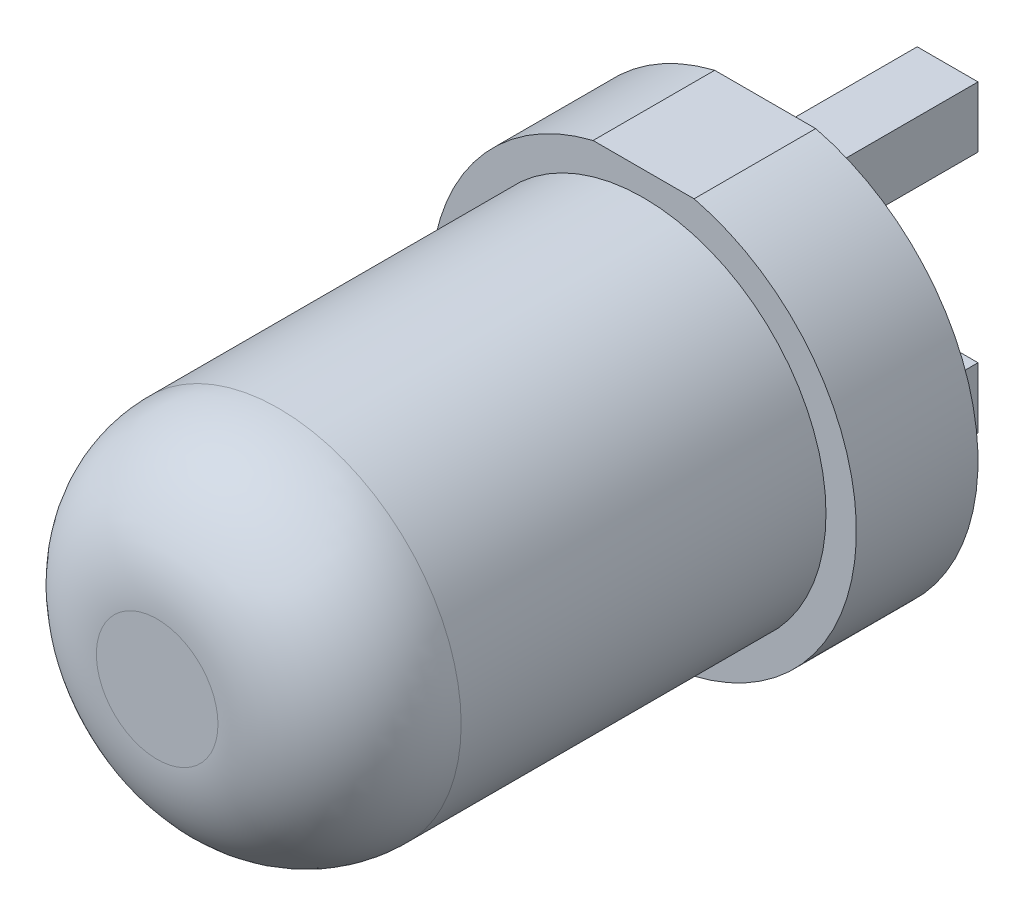
SolidWorks part; units mm, degrees
ref_plane "Front Plane" through (0, 0, 0) normal (0, 0, 1) x (1, 0, 0)
ref_plane "Top Plane" through (0, 0, 0) normal (0, 1, 0) x (1, 0, 0)
ref_plane "Right Plane" through (0, 0, 0) normal (1, 0, 0) x (0, 0, -1)
sketch "Sketch1" plane through (0, 0, 0) normal (0, 0, 1) x (1, 0, 0)
  circle A0 centre (0, 0) radius 1.75
  dimension "D1" = 3.5
extrude "Extrude1" add sketch "Sketch1" along normal mid plane 1
sketch "Sketch2" plane through (0, 0, 0.5) normal (0, 0, 1) x (1, 0, 0)
  circle A0 centre (0, 0) radius 1.5
  dimension "D1" = 3
extrude "Extrude2" add sketch "Sketch2" along normal blind 4
fillet "Fillet2" radius 1 1 edges at (1.5, 0, 4.5)
ref_plane "Plane1" through (0, 3, 0) normal (0, 1, 0) x (-1, 0, 0)
sketch "Sketch4" plane through (0, 3, 0) normal (0, 1, 0) x (-1, 0, 0)
  line L1 (4.5989, -2.7325) -> (-8.4821, -2.7325)
  line L2 (4.5989, -2.7325) -> (4.5989, 3.078)
  line L3 (4.5989, 3.078) -> (-8.4821, 3.078)
  line L4 (-8.4821, -2.7325) -> (-8.4821, 3.078)
extrude "Extrude3" cut sketch "Sketch4" against normal blind 1.3
ref_plane "Plane2" through (0, 0, -0.5) normal (0, 0, -1) x (-1, 0, 0)
sketch "Sketch5" plane through (0, 0, -0.5) normal (0, 0, -1) x (-1, 0, 0)
  line L1 (-0.25, 1.2) -> (0.25, 1.2)
  line L2 (-0.25, 1.2) -> (-0.25, 0.7)
  line L3 (-0.25, 0.7) -> (0.25, 0.7)
  line L4 (0.25, 1.2) -> (0.25, 0.7)
  line L5 (-0.25, -0.8) -> (0.25, -0.8)
  line L6 (-0.25, -0.8) -> (-0.25, -1.3)
  line L7 (-0.25, -1.3) -> (0.25, -1.3)
  line L8 (0.25, -0.8) -> (0.25, -1.3)
  point P10 (0, 1.2)
  point P11 (0, -1.3)
  dimension "D1" = 2.5
  dimension "D2" = 0.5
  dimension "D3" = 0.5
  dimension "D4" = 0.5
  dimension "D5" = 0.5
  dimension "D6" = 0.7
extrude "Extrude4" add sketch "Sketch5" along normal blind 1.5
ref_plane "Plano2" through (0, 0, 0) normal (0, 1, 0) x (-1, 0, 0)
mirror "Simetría1" about plane through (0, 0, 0) normal (0, 1, 0) of "Extrude3"
